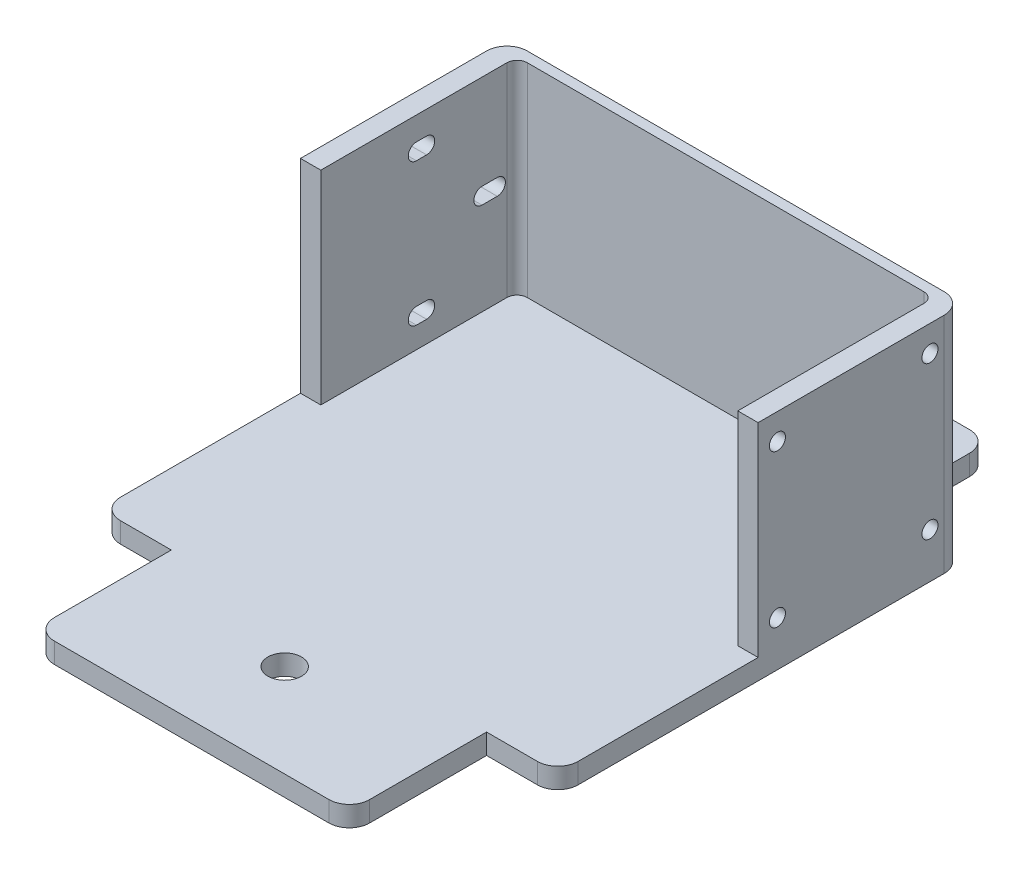
SolidWorks part; units mm, degrees
ref_plane "前视基准面" through (0, 0, 0) normal (0, 0, 1) x (1, 0, 0)
ref_plane "上视基准面" through (0, 0, 0) normal (0, 1, 0) x (1, 0, 0)
ref_plane "右视基准面" through (0, 0, 0) normal (1, 0, 0) x (0, 0, -1)
other "Configuration Table"
sketch "草图1" plane through (0, 0, 0) normal (0, 1, 0) x (1, 0, 0)
  line L5 (-22.5, -20) -> (22.5, -20)
  line L6 (-22.5, -20) -> (-22.5, 20)
  line L7 (-22.5, 20) -> (22.5, 20)
  line L8 (22.5, -20) -> (22.5, 20)
  line L9 (-22.5, -20) -> (22.5, 20) construction
  line L10 (-22.5, 20) -> (22.5, -20) construction
  point P0 (0, 0)
  dimension "D1" = 40
  dimension "D2" = 45
extrude "凸台-拉伸1" add sketch "草图1" along normal blind 2
sketch "草图2" plane through (0, 2, 0) normal (0, 1, 0) x (1, 0, 0)
  line L4 (22.5, -20) -> (22.5, 20)
  line L5 (22.5, -20) -> (22.5, 20)
  line L6 (22.5, 20) -> (-22.5, 20)
  line L7 (22.5, 20) -> (-22.5, 20)
  line L12 (-22.5, -2.3) -> (22.5, -2.3)
  line L13 (-21.5, 19) -> (-21.5, -19)
  line L14 (-21.5, -19) -> (21.5, -19)
  line L15 (21.5, -19) -> (21.5, 19)
  line L16 (21.5, 19) -> (-21.5, 19)
  line L17 (-22.5, 20) -> (-22.5, -20)
  line L18 (-22.5, 20) -> (-22.5, -20)
  line L19 (-22.5, -20) -> (22.5, -20)
  line L20 (-22.5, -20) -> (22.5, -20)
  dimension "D3" = 2.3
  dimension "D1" = 0
  dimension "D2" = 1
extrude "凸台-拉伸2" add sketch "草图2" along normal blind 20
sketch "草图3" plane through (0, 0, 0) normal (0, -1, 0) x (1, 0, 0)
  line L5 (15.5, -29.5) -> (-15.5, -29.5)
  line L6 (15.5, -29.5) -> (15.5, 33.5)
  line L7 (15.5, 33.5) -> (-15.5, 33.5)
  line L8 (-15.5, -29.5) -> (-15.5, 33.5)
  line L9 (15.5, -29.5) -> (-15.5, 33.5) construction
  line L10 (15.5, 33.5) -> (-15.5, -29.5) construction
  point P0 (0, 2)
  dimension "D1" = 63
  dimension "D2" = 31
  dimension "D3" = 2
extrude "凸台-拉伸3" add sketch "草图3" against normal blind 2
sketch "草图4" plane through (0, 0, 0) normal (0, -1, 0) x (1, 0, 0)
  line L0 (-44.325, 0.6) -> (53.0889, 0.6) construction
  line L1 (0, -45.6152) -> (0, 55.5476) construction
  circle A0 centre (0, -23.15) radius 1.65
  circle A1 centre (0, 24.35) radius 1.65
  dimension "D1" = 3.3
  dimension "D2" = 47.5
  dimension "D3" = 0.6
extrude "切除-拉伸1" cut sketch "草图4" against normal blind 2
fillet "圆角2" radius 2 8 edges at (-22.5, 11, -20) (-15.5, 1, -29.5) (15.5, 1, -29.5) (22.5, 1, 20) (15.5, 1, 33.5) (-15.5, 1, 33.5) (-22.5, 1, 20) (22.5, 11, -20)
sketch "草图7" plane through (0, 2, 0) normal (0, 1, 0) x (1, 0, 0)
  line L0 (-22.5, -2.3) -> (22.5, -2.3) construction
  line L1 (-22.5, -2.3) -> (22.5, -2.3)
  line L2 (-20.5, 18) -> (-20.5, -18)
  line L3 (-20.5, -18) -> (20.5, -18)
  line L12 (-22.5, 20) -> (-22.5, -20)
  line L13 (22.5, 20) -> (-22.5, 20)
  line L14 (22.5, -20) -> (22.5, 20)
  line L15 (-22.5, -20) -> (22.5, -20)
  line L16 (-22.5, 20) -> (-22.5, -20)
  line L17 (22.5, 20) -> (-22.5, 20)
  line L18 (22.5, -20) -> (22.5, 20)
  line L19 (-22.5, -20) -> (22.5, -20)
  line L20 (20.5, -18) -> (20.5, 18)
  line L21 (20.5, 18) -> (-20.5, 18)
  line L22 (-21.5, 19) -> (-21.5, -2.3) construction
  line L23 (21.5, -2.3) -> (21.5, 19) construction
  line L24 (21.5, 19) -> (-21.5, 19) construction
  line L25 (-21.5, 19) -> (-21.5, -2.3)
  line L26 (21.5, -2.3) -> (21.5, 19)
  line L27 (21.5, 19) -> (-21.5, 19)
  line L28 (-20.5, 19) -> (-20.5, 18)
  line L29 (20.5, 18) -> (20.5, 19)
  line M25 (21.5, -2.3) -> (21.5, 19)
  line M26 (21.5, 19) -> (-21.5, 19)
  line M27 (-21.5, 19) -> (-21.5, -2.3)
  dimension "D1" = 2
  dimension "D2" = 0
extrude "凸台-拉伸4" add sketch "草图7" along normal up to surface (20 mm away) contours L29 L20 L1 M25 M26 | L28 L27 L1 L2 M27 up to face at (0, 22, -10.5628)
extrude "切除-拉伸2" cut sketch "草图8" along normal up to surface (2.5 mm away)
sketch "草图8" plane through (20, 1.9, 0.9) normal (1, 0, 0) x (0, 1, 0)
  arc A8 (18.3328, -17.5) -> (16.7528, -17.5) centre (17.5428, -17.5) ccw
  arc A9 (16.7528, -17.5) -> (18.3328, -17.5) centre (17.5428, -17.5) ccw
  arc A10 (3.3328, -17.5) -> (1.7528, -17.5) centre (2.5428, -17.5) ccw
  arc A11 (1.7528, -17.5) -> (3.3328, -17.5) centre (2.5428, -17.5) ccw
  arc A12 (3.3328, -2.5) -> (1.7528, -2.5) centre (2.5428, -2.5) ccw
  arc A13 (1.7528, -2.5) -> (3.3328, -2.5) centre (2.5428, -2.5) ccw
  arc A14 (18.3328, -2.5) -> (16.7528, -2.5) centre (17.5428, -2.5) ccw
  arc A15 (16.7528, -2.5) -> (18.3328, -2.5) centre (17.5428, -2.5) ccw
extrude "切除-拉伸3" cut sketch "草图9" along normal up to surface (2.5 mm away)
sketch "草图9" plane through (-20, 1.9, 0.9) normal (-1, 0, 0) x (0, -1, 0)
  arc A6 (-16.21, -10.5011) -> (-17.79, -10.5011) centre (-17, -10.5011) ccw
  arc A7 (-17.79, -10.5011) -> (-16.21, -10.5011) centre (-17, -10.5011) ccw
  arc A8 (-9.21, -17.5) -> (-10.79, -17.5) centre (-10, -17.5) ccw
  arc A9 (-10.79, -17.5) -> (-9.21, -17.5) centre (-10, -17.5) ccw
  arc A10 (-2.21, -10.5011) -> (-3.79, -10.5011) centre (-3, -10.5011) ccw
  arc A11 (-3.79, -10.5011) -> (-2.21, -10.5011) centre (-3, -10.5011) ccw
sketch "草图11" plane through (-22.5, 0, 0) normal (-1, 0, 0) x (0, 0, 1)
  line L0 (2.3, 22) -> (2.3, 2) construction
  line L1 (2.3, 22) -> (2.3, 2)
  line L2 (2.3, 2) -> (0.3, 2)
  line L3 (0.3, 2) -> (0.3, 22)
  line L4 (-18, 22) -> (2.3, 22) construction
  line L5 (0.3, 22) -> (2.3, 22)
  dimension "D1" = 2
extrude "切除-拉伸5" cut sketch "草图11" against normal up to surface (45 mm away) up to face at (22.5, 19.4428, -0.81)
fillet "圆角5" radius 1 2 edges at (-20.5, 12, -19) (20.5, 12, -19)
extrude "切除-拉伸6" cut sketch "草图12" along normal up to surface (2.5 mm away) up to face at (-22.5, 8, 0.1)
sketch "草图12" plane through (-20, 1.9, 0.9) normal (-1, 0, 0) x (0, -1, 0)
  line L0 (-10, -19.4813) -> (-10, -14.8034) construction
  line L1 (-10, -17.95) -> (-10, -16.45) construction
  line L2 (-10.8, -17.95) -> (-10.8, -16.45)
  line L3 (-9.2, -17.95) -> (-9.2, -16.45)
  line L4 (-3, -11.0011) -> (-3, -10.0011) construction
  line L5 (-3.8, -11.0011) -> (-3.8, -10.0011)
  line L6 (-2.2, -11.0011) -> (-2.2, -10.0011)
  line L7 (-17, -11.0011) -> (-17, -10.0011) construction
  line L8 (-17.8, -11.0011) -> (-17.8, -10.0011)
  line L9 (-16.2, -11.0011) -> (-16.2, -10.0011)
  line L11 (-20.1, -18.9) -> (1.9, -18.9) construction
  arc A0 (-10.8, -17.95) -> (-9.2, -17.95) centre (-10, -17.95) ccw
  arc A1 (-9.2, -16.45) -> (-10.8, -16.45) centre (-10, -16.45) ccw
  arc A4 (-16.21, -10.5011) -> (-17.79, -10.5011) centre (-17, -10.5011) ccw construction
  arc A5 (-17.79, -10.5011) -> (-16.21, -10.5011) centre (-17, -10.5011) ccw construction
  arc A8 (-9.21, -17.5) -> (-10.79, -17.5) centre (-10, -17.5) ccw construction
  arc A9 (-10.79, -17.5) -> (-9.21, -17.5) centre (-10, -17.5) ccw construction
  arc A12 (-2.21, -10.5011) -> (-3.79, -10.5011) centre (-3, -10.5011) ccw construction
  arc A13 (-3.79, -10.5011) -> (-2.21, -10.5011) centre (-3, -10.5011) ccw construction
  arc A14 (-3.8, -11.0011) -> (-2.2, -11.0011) centre (-3, -11.0011) ccw
  arc A15 (-2.2, -10.0011) -> (-3.8, -10.0011) centre (-3, -10.0011) ccw
  arc A16 (-17.8, -11.0011) -> (-16.2, -11.0011) centre (-17, -11.0011) ccw
  arc A17 (-16.2, -10.0011) -> (-17.8, -10.0011) centre (-17, -10.0011) ccw
  point P8 (-10, -17.5)
  point P9 (0, 0)
  point P16 (-10, -17.2)
  point P21 (-3, -10.5011)
  point P28 (-17, -10.5011)
  point P35 (0, 0)
  point P36 (-17, -10.5011)
  point P37 (-10, -17.5)
  point P38 (-3, -10.5011)
  point P41 (0, 0)
  point P42 (0, 0)
  point P45 (-10.0048, -16.1698)
  point P46 (0, 0)
  point P47 (-10, -16.7455)
  point P48 (-10, -15.3572)
